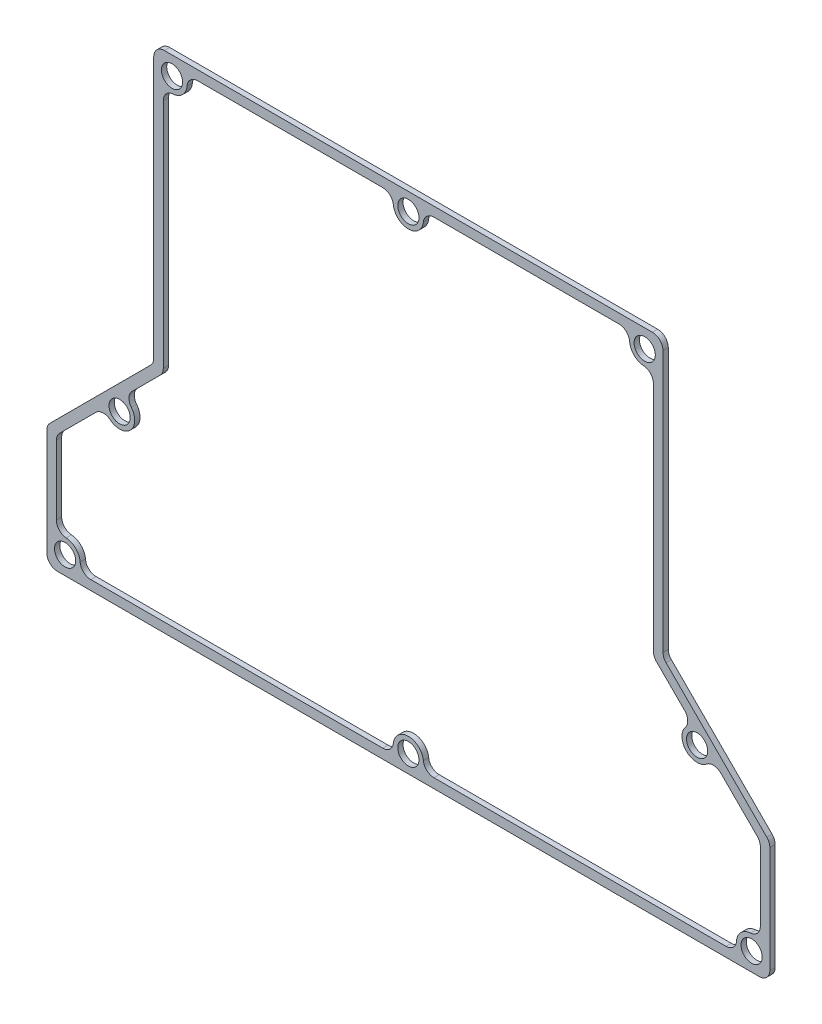
SolidWorks part; units mm, degrees
ref_plane "Front Plane" through (0, 0, 0) normal (0, 0, 1) x (1, 0, 0)
ref_plane "Top Plane" through (0, 0, 0) normal (0, 1, 0) x (1, 0, 0)
ref_plane "Right Plane" through (0, 0, 0) normal (1, 0, 0) x (0, 0, -1)
sketch "Sketch1" plane through (0, 0, 0) normal (0, 0, 1) x (1, 0, 0)
  line L0 (100.5813, -63.0682) -> (100.5813, -13.7887) construction
  line L1 (100.5813, -63.0682) -> (100.5813, -13.7887)
  line L2 (98.5813, -11.7887) -> (6.5263, -11.7887) construction
  line L3 (4.5263, -63.0632) -> (4.5263, -13.7887) construction
  line L4 (-15.0552, -83.4732) -> (3.9406, -64.4774) construction
  line L5 (-15.641, -104.9583) -> (-15.641, -84.8874) construction
  line L6 (-13.641, -106.9583) -> (118.7436, -106.9583) construction
  line L7 (120.7436, -104.9583) -> (120.7436, -84.8874) construction
  line L8 (120.1579, -83.4732) -> (101.1671, -64.4824) construction
  line L9 (98.5813, -11.7887) -> (6.5263, -11.7887)
  line L10 (4.5263, -63.0632) -> (4.5263, -13.7887)
  line L11 (-15.0552, -83.4732) -> (3.9406, -64.4774)
  line L12 (-15.641, -104.9583) -> (-15.641, -84.8874)
  line L13 (-13.641, -106.9583) -> (118.7436, -106.9583)
  line L14 (120.7436, -104.9583) -> (120.7436, -84.8874)
  line L15 (120.1579, -83.4732) -> (101.1671, -64.4824)
  line L16 (98.7813, -63.8138) -> (98.7813, -20.0723) construction
  line L17 (104.666, -70.5269) -> (99.3671, -65.228) construction
  line L18 (118.3579, -84.2187) -> (111.4884, -77.3493) construction
  line L19 (118.9436, -98.6748) -> (118.9436, -85.633) construction
  line L20 (57.3755, -105.1583) -> (112.4601, -105.1583) construction
  line L21 (-7.3604, -105.1583) -> (47.7272, -105.1583) construction
  line L22 (-13.841, -85.633) -> (-13.841, -98.6778) construction
  line L23 (-13.2552, -84.2187) -> (-6.3857, -77.3493) construction
  line L24 (0.4366, -70.5269) -> (5.7406, -65.223) construction
  line L25 (6.3263, -63.8088) -> (6.3263, -20.0723) construction
  line L26 (47.7297, -13.5887) -> (12.8099, -13.5887) construction
  line L27 (92.2978, -13.5887) -> (57.378, -13.5887) construction
  line L28 (98.7813, -63.8138) -> (98.7813, -20.0723)
  line L29 (104.666, -70.5269) -> (99.3671, -65.228)
  line L30 (118.3579, -84.2187) -> (111.4884, -77.3493)
  line L31 (118.9436, -98.6748) -> (118.9436, -85.633)
  line L32 (57.3755, -105.1583) -> (112.4601, -105.1583)
  line L33 (-7.3604, -105.1583) -> (47.7272, -105.1583)
  line L34 (-13.841, -85.633) -> (-13.841, -98.6778)
  line L35 (-13.2552, -84.2187) -> (-6.3857, -77.3493)
  line L36 (0.4366, -70.5269) -> (5.7406, -65.223)
  line L37 (6.3263, -63.8088) -> (6.3263, -20.0723)
  line L38 (47.7297, -13.5887) -> (12.8099, -13.5887)
  line L39 (92.2978, -13.5887) -> (57.378, -13.5887)
  arc A0 (100.5813, -13.7887) -> (98.5813, -11.7887) centre (98.5813, -13.7887) ccw construction
  arc A1 (6.5263, -11.7887) -> (4.5263, -13.7887) centre (6.5263, -13.7887) ccw construction
  arc A2 (3.9406, -64.4774) -> (4.5263, -63.0632) centre (2.5263, -63.0632) ccw construction
  arc A3 (-15.0552, -83.4732) -> (-15.641, -84.8874) centre (-13.641, -84.8874) ccw construction
  arc A4 (-15.641, -104.9583) -> (-13.641, -106.9583) centre (-13.641, -104.9583) ccw construction
  arc A5 (118.7436, -106.9583) -> (120.7436, -104.9583) centre (118.7436, -104.9583) ccw construction
  arc A6 (120.7436, -84.8874) -> (120.1579, -83.4732) centre (118.7436, -84.8874) ccw construction
  arc A7 (100.5813, -63.0682) -> (101.1671, -64.4824) centre (102.5813, -63.0682) ccw construction
  arc A8 (100.5813, -13.7887) -> (98.5813, -11.7887) centre (98.5813, -13.7887) ccw
  arc A9 (6.5263, -11.7887) -> (4.5263, -13.7887) centre (6.5263, -13.7887) ccw
  arc A10 (3.9406, -64.4774) -> (4.5263, -63.0632) centre (2.5263, -63.0632) ccw
  arc A11 (-15.0552, -83.4732) -> (-15.641, -84.8874) centre (-13.641, -84.8874) ccw
  arc A12 (-15.641, -104.9583) -> (-13.641, -106.9583) centre (-13.641, -104.9583) ccw
  arc A13 (118.7436, -106.9583) -> (120.7436, -104.9583) centre (118.7436, -104.9583) ccw
  arc A14 (120.7436, -84.8874) -> (120.1579, -83.4732) centre (118.7436, -84.8874) ccw
  arc A15 (100.5813, -63.0682) -> (101.1671, -64.4824) centre (102.5813, -63.0682) ccw
  arc A16 (98.7813, -63.8138) -> (99.3671, -65.228) centre (100.7813, -63.8138) ccw construction
  arc A17 (104.8043, -73.202) -> (104.666, -70.5269) centre (103.2518, -71.9411) ccw construction
  arc A18 (104.8043, -73.202) -> (108.8133, -77.211) centre (107.0166, -74.9988) ccw construction
  arc A19 (111.4884, -77.3493) -> (108.8133, -77.211) centre (110.0742, -78.7635) ccw construction
  arc A20 (118.9436, -85.633) -> (118.3579, -84.2187) centre (116.9436, -85.633) ccw construction
  arc A21 (117.0894, -100.6695) -> (118.9436, -98.6748) centre (116.9436, -98.6748) ccw construction
  arc A22 (117.0894, -100.6695) -> (114.4548, -103.3041) centre (117.2972, -103.5119) ccw construction
  arc A23 (112.4601, -105.1583) -> (114.4548, -103.3041) centre (112.4601, -103.1583) ccw construction
  arc A24 (55.3862, -103.3645) -> (57.3755, -105.1583) centre (57.3755, -103.1583) ccw construction
  arc A25 (55.3862, -103.3645) -> (49.7165, -103.3645) centre (52.5513, -103.6583) ccw construction
  arc A26 (47.7272, -105.1583) -> (49.7165, -103.3645) centre (47.7272, -103.1583) ccw construction
  arc A27 (-9.355, -103.3047) -> (-7.3604, -105.1583) centre (-7.3604, -103.1583) ccw construction
  arc A28 (-9.355, -103.3047) -> (-11.9873, -100.6724) centre (-12.1957, -103.5131) ccw construction
  arc A29 (-13.841, -98.6778) -> (-11.9873, -100.6724) centre (-11.841, -98.6778) ccw construction
  arc A30 (-13.2552, -84.2187) -> (-13.841, -85.633) centre (-11.841, -85.633) ccw construction
  arc A31 (-3.7106, -77.211) -> (-6.3857, -77.3493) centre (-4.9715, -78.7635) ccw construction
  arc A32 (-3.7106, -77.211) -> (0.2984, -73.202) centre (-1.9139, -74.9988) ccw construction
  arc A33 (0.4366, -70.5269) -> (0.2984, -73.202) centre (1.8509, -71.9411) ccw construction
  arc A34 (5.7406, -65.223) -> (6.3263, -63.8088) centre (4.3263, -63.8088) ccw construction
  arc A35 (8.1805, -18.0776) -> (6.3263, -20.0723) centre (8.3263, -20.0723) ccw construction
  arc A36 (8.1805, -18.0776) -> (10.8152, -15.4429) centre (7.9728, -15.2352) ccw construction
  arc A37 (12.8099, -13.5887) -> (10.8152, -15.4429) centre (12.8099, -15.5887) ccw construction
  arc A38 (49.719, -15.3825) -> (47.7297, -13.5887) centre (47.7297, -15.5887) ccw construction
  arc A39 (49.719, -15.3825) -> (55.3887, -15.3825) centre (52.5538, -15.0887) ccw construction
  arc A40 (57.378, -13.5887) -> (55.3887, -15.3825) centre (57.378, -15.5887) ccw construction
  arc A41 (94.2925, -15.4429) -> (92.2978, -13.5887) centre (92.2978, -15.5887) ccw construction
  arc A42 (94.2925, -15.4429) -> (96.9271, -18.0776) centre (97.1349, -15.2352) ccw construction
  arc A43 (98.7813, -20.0723) -> (96.9271, -18.0776) centre (96.7813, -20.0723) ccw construction
  arc A44 (98.7813, -63.8138) -> (99.3671, -65.228) centre (100.7813, -63.8138) ccw
  arc A45 (104.8043, -73.202) -> (104.666, -70.5269) centre (103.2518, -71.9411) ccw
  arc A46 (104.8043, -73.202) -> (108.8133, -77.211) centre (107.0166, -74.9988) ccw
  arc A47 (111.4884, -77.3493) -> (108.8133, -77.211) centre (110.0742, -78.7635) ccw
  arc A48 (118.9436, -85.633) -> (118.3579, -84.2187) centre (116.9436, -85.633) ccw
  arc A49 (117.0894, -100.6695) -> (118.9436, -98.6748) centre (116.9436, -98.6748) ccw
  arc A50 (117.0894, -100.6695) -> (114.4548, -103.3041) centre (117.2972, -103.5119) ccw
  arc A51 (112.4601, -105.1583) -> (114.4548, -103.3041) centre (112.4601, -103.1583) ccw
  arc A52 (55.3862, -103.3645) -> (57.3755, -105.1583) centre (57.3755, -103.1583) ccw
  arc A53 (55.3862, -103.3645) -> (49.7165, -103.3645) centre (52.5513, -103.6583) ccw
  arc A54 (47.7272, -105.1583) -> (49.7165, -103.3645) centre (47.7272, -103.1583) ccw
  arc A55 (-9.355, -103.3047) -> (-7.3604, -105.1583) centre (-7.3604, -103.1583) ccw
  arc A56 (-9.355, -103.3047) -> (-11.9873, -100.6724) centre (-12.1957, -103.5131) ccw
  arc A57 (-13.841, -98.6778) -> (-11.9873, -100.6724) centre (-11.841, -98.6778) ccw
  arc A58 (-13.2552, -84.2187) -> (-13.841, -85.633) centre (-11.841, -85.633) ccw
  arc A59 (-3.7106, -77.211) -> (-6.3857, -77.3493) centre (-4.9715, -78.7635) ccw
  arc A60 (-3.7106, -77.211) -> (0.2984, -73.202) centre (-1.9139, -74.9988) ccw
  arc A61 (0.4366, -70.5269) -> (0.2984, -73.202) centre (1.8509, -71.9411) ccw
  arc A62 (5.7406, -65.223) -> (6.3263, -63.8088) centre (4.3263, -63.8088) ccw
  arc A63 (8.1805, -18.0776) -> (6.3263, -20.0723) centre (8.3263, -20.0723) ccw
  arc A64 (8.1805, -18.0776) -> (10.8152, -15.4429) centre (7.9728, -15.2352) ccw
  arc A65 (12.8099, -13.5887) -> (10.8152, -15.4429) centre (12.8099, -15.5887) ccw
  arc A66 (49.719, -15.3825) -> (47.7297, -13.5887) centre (47.7297, -15.5887) ccw
  arc A67 (49.719, -15.3825) -> (55.3887, -15.3825) centre (52.5538, -15.0887) ccw
  arc A68 (57.378, -13.5887) -> (55.3887, -15.3825) centre (57.378, -15.5887) ccw
  arc A69 (94.2925, -15.4429) -> (92.2978, -13.5887) centre (92.2978, -15.5887) ccw
  arc A70 (94.2925, -15.4429) -> (96.9271, -18.0776) centre (97.1349, -15.2352) ccw
  arc A71 (98.7813, -20.0723) -> (96.9271, -18.0776) centre (96.7813, -20.0723) ccw
  circle A72 centre (-12.1957, -103.5131) radius 2
  circle A73 centre (52.5513, -103.6583) radius 2
  circle A74 centre (117.2972, -103.5119) radius 2
  circle A75 centre (107.0166, -74.9988) radius 2
  circle A76 centre (-1.9139, -74.9988) radius 2
  circle A77 centre (7.9728, -15.2352) radius 2
  circle A78 centre (52.5538, -15.0887) radius 2
  circle A79 centre (97.1349, -15.2352) radius 2
extrude "Boss-Extrude1" add sketch "Sketch1" along normal blind 1 contours A15 L1 A8 L9 A9 L10 A10 L11 A11 L12 A12 L13 A13 L14 A14 L15 A79 A78 A77 A76 A75 A74 A73 A72 A71 L28 A44 L29 A45 A46 A47 L30 A48 L31 A49 A50 A51 L32 A52 A53 A54 L33
